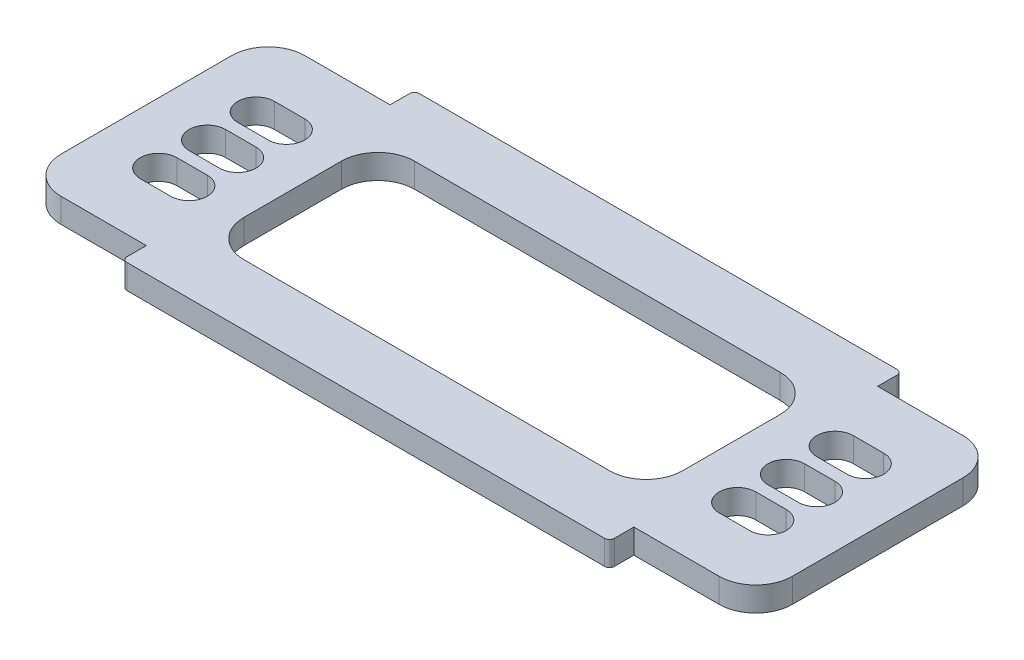
SolidWorks part; units mm, degrees
material "Thornel Mat VMA"
ref_plane "前视基准面" through (0, 0, 0) normal (0, 0, 1) x (1, 0, 0)
ref_plane "上视基准面" through (0, 0, 0) normal (0, 1, 0) x (1, 0, 0)
ref_plane "右视基准面" through (0, 0, 0) normal (1, 0, 0) x (0, 0, -1)
other "Configuration Table"
sketch "草图1" plane through (0, 0, 0) normal (0, 1, 0) x (1, 0, 0)
  line L1 (-20, -12) -> (20, -12)
  line L2 (-20, -12) -> (-20, 12)
  line L3 (-20, 12) -> (20, 12)
  line L4 (20, -12) -> (20, 12)
  line L5 (-20, -12) -> (20, 12) construction
  line L6 (-20, 12) -> (20, -12) construction
  point P0 (0, 0)
  dimension "D1" = 40
  dimension "D2" = 24
extrude "凸台-拉伸1" add sketch "草图1" along normal blind 2
sketch "草图4" plane through (0, 2, 0) normal (0, 1, 0) x (1, 0, 0)
  line L4 (-30, -10) -> (30, -10)
  line L5 (-30, -10) -> (-30, 10)
  line L6 (-30, 10) -> (30, 10)
  line L7 (30, -10) -> (30, 10)
  line L8 (-30, -10) -> (30, 10) construction
  line L9 (-30, 10) -> (30, -10) construction
  point P0 (0, 0)
  dimension "D4" = 0
  dimension "D1" = 20
  dimension "D2" = 60
  dimension "D3" = 0
extrude "凸台-拉伸3" add sketch "草图4" against normal blind 2
sketch "草图6" plane through (0, 2, 0) normal (0, 1, 0) x (1, 0, 0)
  line L1 (-25, 0) -> (-22.5, 0) construction
  line L2 (-25, 1.5) -> (-22.5, 1.5)
  line L3 (-25, -1.5) -> (-22.5, -1.5)
  line L4 (-25, 4) -> (-22.5, 4) construction
  line L5 (-25, 5.5) -> (-22.5, 5.5)
  line L6 (-25, 2.5) -> (-22.5, 2.5)
  line L7 (-25, -4) -> (-22.5, -4) construction
  line L8 (-25, -2.5) -> (-22.5, -2.5)
  line L9 (-25, -5.5) -> (-22.5, -5.5)
  line L10 (0, -1000) -> (0, 49000) construction
  line L11 (25, -4) -> (22.5, -4) construction
  line L12 (25, -2.5) -> (22.5, -2.5)
  line L13 (25, -5.5) -> (22.5, -5.5)
  line L14 (25, 0) -> (22.5, 0) construction
  line L15 (25, 1.5) -> (22.5, 1.5)
  line L16 (25, -1.5) -> (22.5, -1.5)
  line L17 (25, 4) -> (22.5, 4) construction
  line L18 (25, 5.5) -> (22.5, 5.5)
  line L19 (25, 2.5) -> (22.5, 2.5)
  arc A3 (-25, 1.5) -> (-25, -1.5) centre (-25, 0) ccw
  arc A4 (-22.5, -1.5) -> (-22.5, 1.5) centre (-22.5, 0) ccw
  arc A5 (-25, 5.5) -> (-25, 2.5) centre (-25, 4) ccw
  arc A6 (-22.5, 2.5) -> (-22.5, 5.5) centre (-22.5, 4) ccw
  arc A7 (-25, -2.5) -> (-25, -5.5) centre (-25, -4) ccw
  arc A8 (-22.5, -5.5) -> (-22.5, -2.5) centre (-22.5, -4) ccw
  arc A9 (25, -2.5) -> (25, -5.5) centre (25, -4) cw
  arc A10 (22.5, -5.5) -> (22.5, -2.5) centre (22.5, -4) cw
  arc A11 (25, 1.5) -> (25, -1.5) centre (25, 0) cw
  arc A12 (22.5, -1.5) -> (22.5, 1.5) centre (22.5, 0) cw
  arc A13 (25, 5.5) -> (25, 2.5) centre (25, 4) cw
  arc A14 (22.5, 2.5) -> (22.5, 5.5) centre (22.5, 4) cw
  point P2 (-23.75, 0)
  point P11 (-23.75, 4)
  point P18 (-23.75, -4)
  point P27 (23.75, -4)
  point P34 (23.75, 0)
  point P41 (23.75, 4)
  dimension "D1" = 25
  dimension "D2" = 22.5
  dimension "D3" = 1.5
extrude "切除-拉伸3" cut sketch "草图6" against normal through all
sketch "草图7" plane through (0, 2, 0) normal (0, 1, 0) x (1, 0, 0)
  line L0 (20, 12) -> (-20, 12) construction
  line L1 (-18, -7) -> (18, -7)
  line L2 (-18, -7) -> (-18, 7)
  line L3 (-18, 7) -> (18, 7)
  line L4 (18, -7) -> (18, 7)
  line L5 (-18, -7) -> (18, 7) construction
  line L6 (-18, 7) -> (18, -7) construction
  arc A0 (-22.5, -1.5) -> (-22.5, 1.5) centre (-22.5, 0) ccw construction
  point P0 (0, 0)
  point P11 (-21, 0)
  dimension "D1" = 5
  dimension "D2" = 3
extrude "切除-拉伸4" cut sketch "草图7" against normal through all
fillet "圆角1" radius 3 8 edges at (30, 1, 10) (30, 1, -10) (-30, 1, 10) (-30, 1, -10) (-18, 1, -7) (18, 1, -7) (18, 1, 7) (-18, 1, 7)
fillet "圆角2" radius 0.4 4 edges at (-20, 1, 12) (20, 1, 12) (20, 1, -12) (-20, 1, -12)
